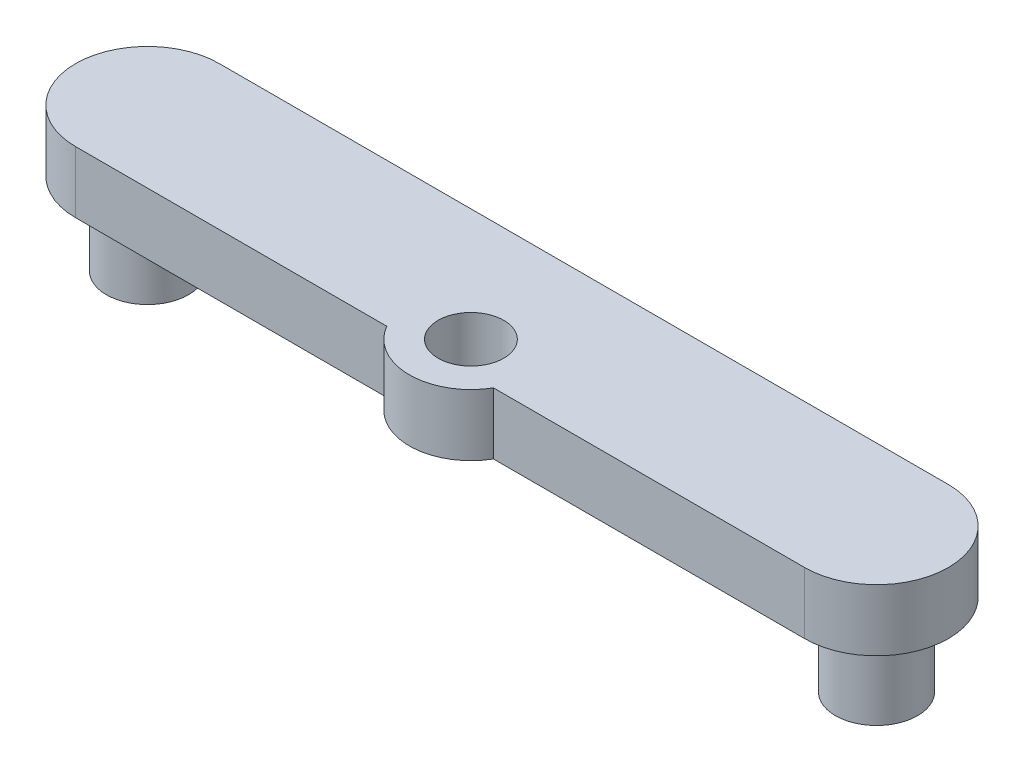
SolidWorks part; units mm, degrees
ref_plane "Front Plane" through (0, 0, 0) normal (0, 0, 1) x (1, 0, 0)
ref_plane "Top Plane" through (0, 0, 0) normal (0, 1, 0) x (1, 0, 0)
ref_plane "Right Plane" through (0, 0, 0) normal (1, 0, 0) x (0, 0, -1)
sketch "Sketch1" plane through (0, 0, 0) normal (0, 1, 0) x (1, 0, 0)
  line L0 (17.75, 0) -> (-17.75, 0) construction
  line L1 (17.75, -3.5) -> (-17.75, -3.5)
  line L2 (17.75, 3.5) -> (-17.75, 3.5)
  arc A3 (17.75, -3.5) -> (17.75, 3.5) centre (17.75, 0) ccw
  arc A4 (-17.75, 3.5) -> (-17.75, -3.5) centre (-17.75, 0) ccw
  circle A5 centre (0, -2) radius 1.6
  circle A6 centre (0, -2) radius 3
  point P3 (0, 0)
  dimension "D2" = 3.5
  dimension "D4" = 3.2
  dimension "D5" = 6
  dimension "D1" = 35.5
  dimension "D3" = 2
  dimension "D6" = 17.75
extrude "Boss-Extrude1" add sketch "Sketch1" along normal blind 3
sketch "Sketch2" plane through (0, 0, 0) normal (0, -1, 0) x (1, 0, 0)
  line L0 (-17.75, 0) -> (17.75, 0) construction
  circle A0 centre (-17.75, 0) radius 2
  circle A1 centre (17.75, 0) radius 2
  dimension "D1" = 4
extrude "Boss-Extrude2" add sketch "Sketch2" along normal blind 4
